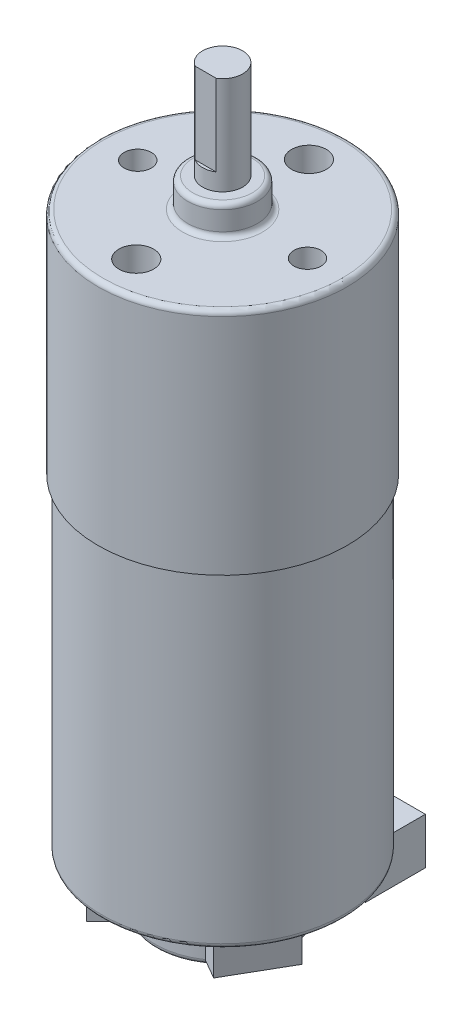
SolidWorks part; units mm, degrees
ref_plane "Alzado" through (0, 0, 0) normal (0, 0, 1) x (1, 0, 0)
ref_plane "Planta" through (0, 0, 0) normal (0, 1, 0) x (1, 0, 0)
ref_plane "Vista lateral" through (0, 0, 0) normal (1, 0, 0) x (0, 0, -1)
sketch "Croquis1" plane through (0, 0, 0) normal (0, 1, 0) x (1, 0, 0)
  circle A0 centre (0, 0) radius 12.065
  dimension "D1" = 24.13
extrude "Saliente-Extruir1" add sketch "Croquis1" along normal blind 31.01
sketch "Croquis2" plane through (0, 31.01, 0) normal (0, 1, 0) x (1, 0, 0)
  circle A0 centre (0, 0) radius 12.44
  dimension "D1" = 24.88
extrude "Saliente-Extruir2" add sketch "Croquis2" along normal blind 22.88
sketch "Croquis3" plane through (0, 0, 0) normal (0, -1, 0) x (1, 0, 0)
  circle A0 centre (0, 0) radius 12.065
extrude "Saliente-Extruir3" add sketch "Croquis3" along normal blind 1.63
sketch "Croquis4" plane through (0, 53.89, 0) normal (0, 1, 0) x (1, 0, 0)
  circle A0 centre (0, 0) radius 3.475
  dimension "D1" = 6.95
extrude "Saliente-Extruir4" add sketch "Croquis4" along normal blind 2.91
sketch "Croquis5" plane through (0, 56.8, 0) normal (0, 1, 0) x (1, 0, 0)
  circle A0 centre (0, 0) radius 2
  dimension "D1" = 4
extrude "Saliente-Extruir5" add sketch "Croquis5" along normal blind 9.8
sketch "Croquis6" plane through (0, -1.63, 0) normal (0, -1, 0) x (1, 0, 0)
  circle A0 centre (0, 0) radius 6.725
  dimension "D1" = 13.45
extrude "Saliente-Extruir6" add sketch "Croquis6" along normal blind 5.22
sketch "Croquis7" plane through (0, -1.63, 0) normal (0, -1, 0) x (1, 0, 0)
  line L0 (0, -12.065) -> (0, 12.065) construction
  line L1 (0, 0) -> (-8.5312, 8.5312) construction
  line L2 (-9.0893, 4.5214) -> (-4.5214, 9.0893)
  line L3 (-4.5214, 9.0893) -> (-2.8951, 7.463)
  line L4 (-2.8951, 7.463) -> (-7.463, 2.8951)
  line L5 (-7.463, 2.8951) -> (-9.0893, 4.5214)
  line L6 (0, 0) -> (10.4486, 6.0325) construction
  line L7 (9.9462, 2.0127) -> (6.7162, 7.6073)
  line L8 (6.7162, 7.6073) -> (4.7243, 6.4573)
  line L9 (4.7243, 6.4573) -> (7.9543, 0.8627)
  line L10 (7.9543, 0.8627) -> (9.9462, 2.0127)
  circle A0 centre (0, 0) radius 12.065 construction
  circle A1 centre (0, 0) radius 12.065 construction
  circle A3 centre (0, 0) radius 6.725 construction
  point P13 (-6.8054, 6.8054)
  point P16 (-4.5214, 9.0893)
  point P22 (8.3312, 4.81)
  dimension "D1" = 45
  dimension "D2" = 6.46
  dimension "D3" = 2.3
  dimension "D4" = 7.3242
  dimension "D5" = 60
  dimension "D6" = 6.46
  dimension "D7" = 2.3
  dimension "D8" = 7.32
extrude "Saliente-Extruir7" add sketch "Croquis7" along normal blind 3.83
sketch "Croquis9" plane through (0, -1.63, 0) normal (0, -1, 0) x (1, 0, 0)
  line L0 (0, 12.065) -> (0, -12.44) construction
  line L2 (-6.95, -7.3046) -> (6.95, -7.3046)
  line L3 (-6.95, -7.3046) -> (-6.95, -13.3046)
  line L4 (-6.95, -13.3046) -> (6.95, -13.3046)
  line L5 (6.95, -7.3046) -> (6.95, -13.3046)
  circle A0 centre (0, 0) radius 12.065 construction
  circle A1 centre (0, 0) radius 12.44 construction
  circle A2 centre (0, 0) radius 6.725 construction
  point P13 (0, -7.3046)
  dimension "D1" = 7.3046
  dimension "D2" = 6
  dimension "D3" = 13.9
extrude "Saliente-Extruir8" add sketch "Croquis9" along normal blind 4.64
sketch "Croquis12" plane through (0, -6.27, 0) normal (0, -1, 0) x (1, 0, 0)
  line L0 (-6.95, -13.3046) -> (6.95, -13.3046) construction
  line L1 (-4.02, -13.3046) -> (4.02, -13.3046)
  line L2 (-4.02, -13.3046) -> (-4.02, -8.8285)
  line L3 (-4.02, -8.8285) -> (4.02, -8.8285)
  line L4 (4.02, -13.3046) -> (4.02, -8.8285)
  line L5 (-6.95, -7.3046) -> (-6.95, -13.3046) construction
  line L7 (6.95, -13.3046) -> (6.95, -7.3046) construction
  dimension "D1" = 2.93
  dimension "D2" = 2.93
extrude "Cortar-Extruir1" cut sketch "Croquis12" against normal blind 1
sketch "Croquis13" plane through (0, 53.89, 0) normal (0, 1, 0) x (1, 0, 0)
  line L0 (0, 12.065) -> (0, -12.44) construction
  line L1 (-12.44, 0) -> (12.44, 0) construction
  line L2 (0, 12.065) -> (-10.741, 12.065) construction
  line L3 (0, 10.365) -> (12.1, 10.365) construction
  line L4 (-12.44, 0) -> (-12.44, -8.5889) construction
  line L5 (-9.84, 0) -> (-9.84, 9.7707) construction
  arc A0 (6.95, 9.8621) -> (-6.95, 9.8621) centre (0, 0) ccw construction
  circle A1 centre (0, 0) radius 12.44 construction
  circle A2 centre (0, 8.6278) radius 1.7372
  circle A3 centre (-8.48, 0) radius 1.36
  circle A4 centre (0, -8.6278) radius 1.7372
  circle A5 centre (8.48, 0) radius 1.36
  dimension "D1" = 2.72
  dimension "D3" = 1.7
  dimension "D4" = 2.6
extrude "Cortar-Extruir2" cut sketch "Croquis13" against normal blind 10
sketch "Croquis15" plane through (0, 0, -13.3046) normal (0, 0, -1) x (-1, 0, 0)
  line L0 (-6.95, -6.27) -> (-6.95, -1.63) construction
  line L1 (-6.35, -2.23) -> (6.35, -2.23)
  line L2 (-6.35, -2.23) -> (-6.35, -5.67)
  line L3 (-6.35, -5.67) -> (6.35, -5.67)
  line L4 (6.35, -2.23) -> (6.35, -5.67)
  line L5 (6.95, -6.27) -> (6.95, -1.63) construction
  line L7 (6.95, -1.63) -> (-6.95, -1.63) construction
  line L8 (-4.02, -6.27) -> (-6.95, -6.27) construction
  dimension "D1" = 0.6
  dimension "D2" = 0.6
  dimension "D3" = 0.6
  dimension "D4" = 0.6
extrude "Cortar-Extruir3" cut sketch "Croquis15" against normal blind 4.48
sketch "Croquis16" plane through (0, 0, -8.8246) normal (0, 0, -1) x (-1, 0, 0)
  line L0 (-4.58, -3.63) -> (-6.35, -3.63) construction
  line L1 (-6.35, -2.23) -> (-6.35, -5.67) construction
  line L3 (-6.35, -2.23) -> (-6.35, -5.67) construction
  line L4 (-4.88, -3.93) -> (-4.88, -7.9182) construction
  line L5 (6.35, -2.23) -> (-6.35, -2.23) construction
  circle A0 centre (-4.58, -3.93) radius 0.3
  circle A1 centre (-2.78, -3.93) radius 0.3
  circle A2 centre (-0.98, -3.93) radius 0.3
  circle A3 centre (0.82, -3.93) radius 0.3
  circle A4 centre (2.62, -3.93) radius 0.3
  circle A5 centre (4.42, -3.93) radius 0.3
  dimension "D1" = 0.6
  dimension "D2" = 1.47
  dimension "D3" = 1.4
extrude "Saliente-Extruir10" add sketch "Croquis16" along normal blind 4.38
fillet "Redondeo1" radius 0.5 4 edges at (0, 53.89, 12.44) (0, 56.8, 3.475) (0, 53.89, 3.475) (0, -1.63, 12.065)
fillet "Redondeo2" radius 0.5 1 edges at (0, -6.85, -6.725)
ref_plane "Plano1" through (0, 0, 2) normal (0, 0, 1) x (1, 0, 0)
sketch "Croquis17" plane through (0, 0, 2) normal (0, 0, 1) x (1, 0, 0)
  line L0 (2, 56.8) -> (-2, 56.8) construction
  line L1 (-1.9976, 58.49) -> (2, 58.49)
  line L2 (-1.9976, 58.49) -> (-1.9976, 66.6)
  line L3 (-1.9976, 66.6) -> (2, 66.6)
  line L4 (2, 58.49) -> (2, 66.6)
  dimension "D1" = 1.69
extrude "Cortar-Extruir4" cut sketch "Croquis17" against normal blind 0.3
